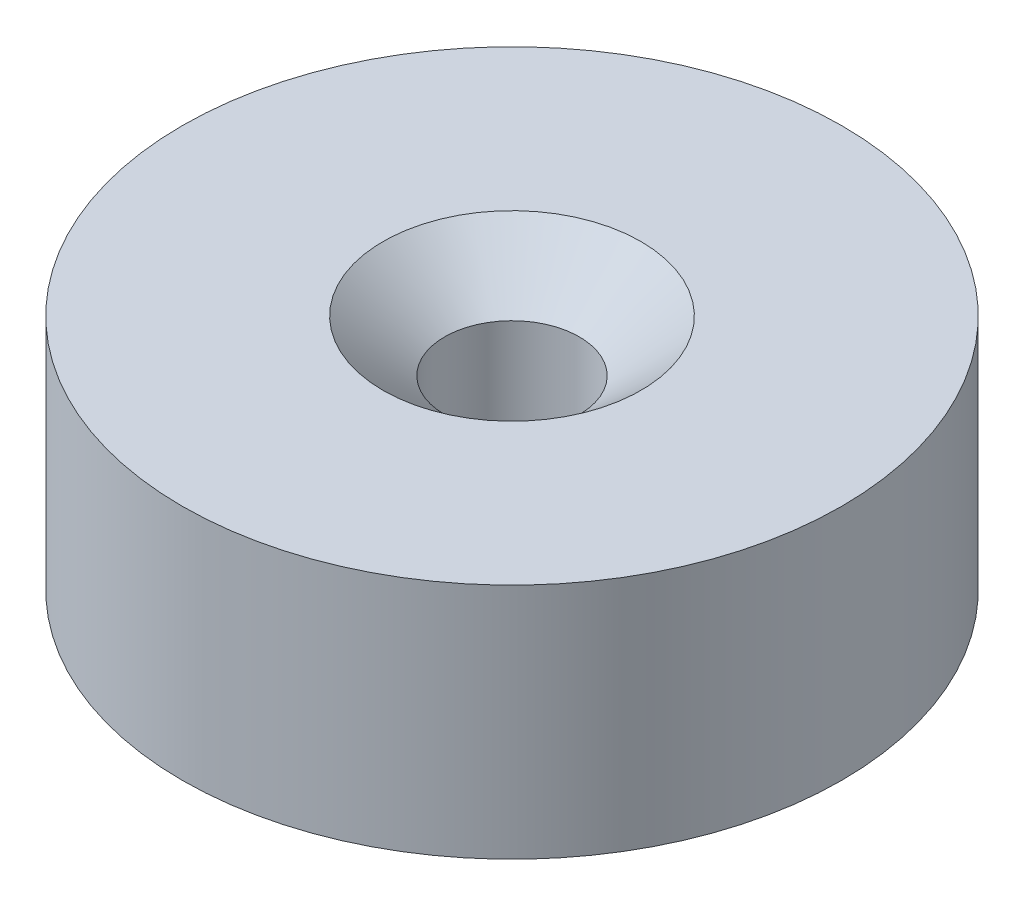
SolidWorks part; units mm, degrees
ref_plane "Front Plane" through (0, 0, 0) normal (0, 0, 1) x (1, 0, 0)
ref_plane "Top Plane" through (0, 0, 0) normal (0, 1, 0) x (1, 0, 0)
ref_plane "Right Plane" through (0, 0, 0) normal (1, 0, 0) x (0, 0, -1)
sketch "Sketch1" plane through (0, 0, 0) normal (0, 1, 0) x (1, 0, 0)
  circle A0 centre (0, 0) radius 2
  circle A1 centre (0, 0) radius 12.5
  dimension "D1" = 25
  dimension "D2" = 4
extrude "Boss-Extrude1" add sketch "Sketch1" along normal blind 9
hole_wizard "CSK for #10 Flat Head Machine Screw (100)1" positions "Sketch2" profile "Sketch3" countersink size "#10" standard "ANSI Inch" end condition through all
sketch "Sketch2" plane through (0, 9, 0) normal (0, 1, 0) x (1, 0, 0)
  point P0 (0, 0)
sketch "Sketch3" plane through (0, 9, 0) normal (1, 0, 0) x (0, 0, 1)
  line L0 (0, 0) -> (0, 9)
  line L1 (0, 9) -> (2.5527, 9)
  line L2 (2.5527, 9) -> (2.5527, 1.9608)
  line L3 (2.5527, 1.9608) -> (4.8895, 0)
  line L5 (4.8895, 0) -> (0, 0)
  line L6 (-2.5527, 1.9608) -> (-4.8895, 0) construction
  line L11 (0, -6.35) -> (0, 107.95) construction
  dimension "Thru Hole Dia." = 5.1054
  dimension "Thru Hole Depth" = 9
  dimension "Near C'Sink Dia." = 9.779
  dimension "Near C'Sink Angle" = 100
